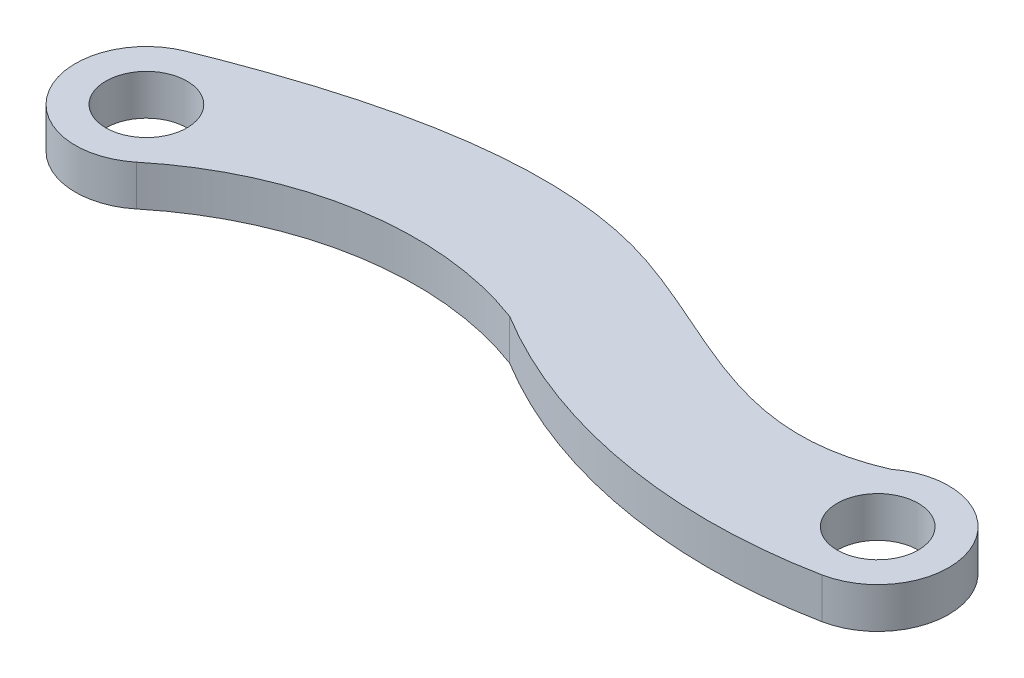
SolidWorks part; units mm, degrees
ref_plane "Front Plane" through (0, 0, 0) normal (0, 0, 1) x (1, 0, 0)
ref_plane "Top Plane" through (0, 0, 0) normal (0, 1, 0) x (1, 0, 0)
ref_plane "Right Plane" through (0, 0, 0) normal (1, 0, 0) x (0, 0, -1)
sketch "Sketch2" plane through (0, 0, 0) normal (0, 1, 0) x (1, 0, 0)
  circle A0 centre (-26.6348, 6.4614) radius 2
  circle A1 centre (9.4152, 6.4614) radius 2
  arc A2 (-27.927, 9.7141) -> (-24.4122, 3.7577) centre (-26.6348, 6.4614) ccw
  arc A3 (-8.6357, 6.3682) -> (10.0908, 3.0272) centre (5.0242, 28.7803) ccw
  arc A4 (10.0908, 3.0272) -> (7.2765, 9.2319) centre (9.4152, 6.4614) ccw
  arc A6 (-8.6357, 6.3682) -> (-24.4122, 3.7577) centre (-14.2657, -8.5846) ccw
  spline S0 degree 3 poles (7.2765, 9.2319) (4.9917, 8.2394) (-0.3849, 8.3923) (-11.3003, 15.2339) (-22.1957, 12.0137) (-27.927, 9.7141) knots 0.029474 0.029474 0.029474 0.029474 0.20528 0.474214 1 1 1 1
  dimension "D1" = 4
  dimension "D2" = 4
  dimension "D3" = 7
  dimension "D4" = 7
  dimension "D5" = 36.05
extrude "Boss-Extrude1" add sketch "Sketch2" along normal blind 2
